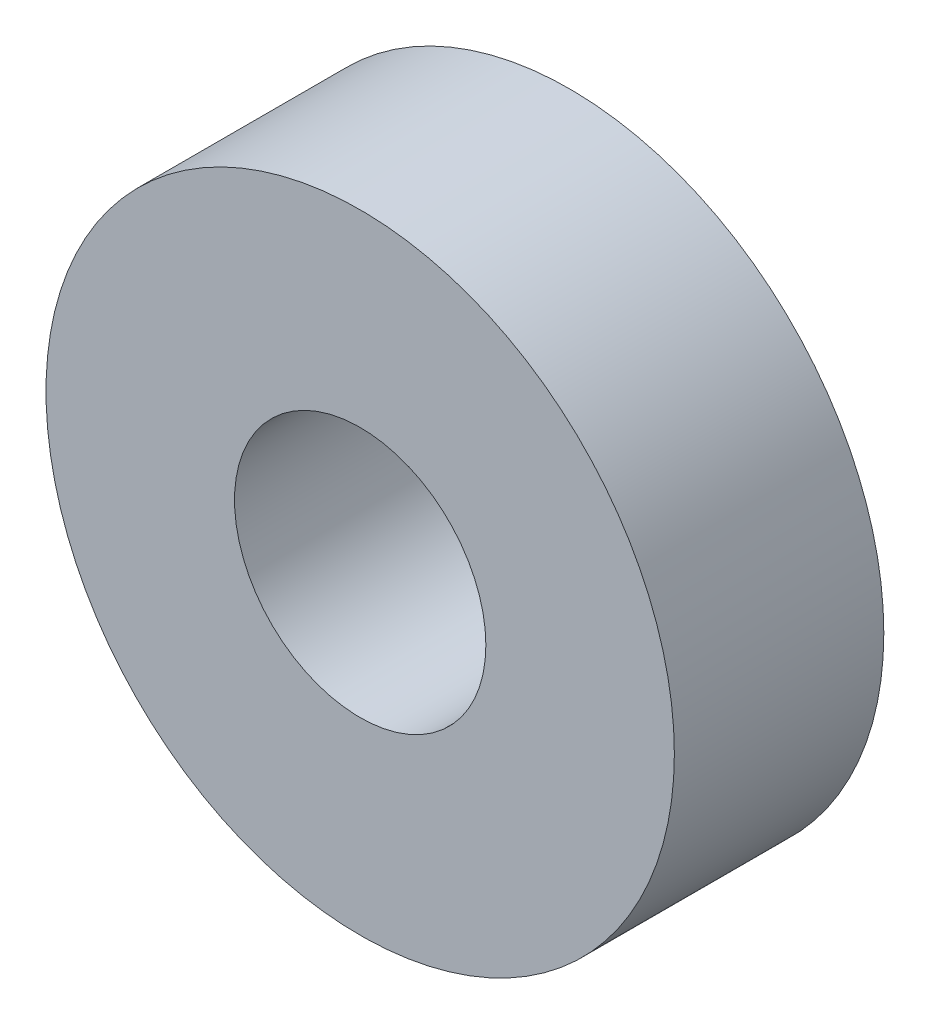
SolidWorks part; units mm, degrees
ref_plane "Спереди" through (0, 0, 0) normal (0, 0, 1) x (1, 0, 0)
ref_plane "Сверху" through (0, 0, 0) normal (0, 1, 0) x (1, 0, 0)
ref_plane "Справа" through (0, 0, 0) normal (1, 0, 0) x (0, 0, -1)
sketch "Эскиз1" plane through (0, 0, 0) normal (0, 0, 1) x (1, 0, 0)
  circle A0 centre (0, 0) radius 7.5
  circle A1 centre (0, 0) radius 3
  dimension "D1" = 6
  dimension "D2" = 15
extrude "Бобышка-Вытянуть1" add sketch "Эскиз1" along normal blind 5
